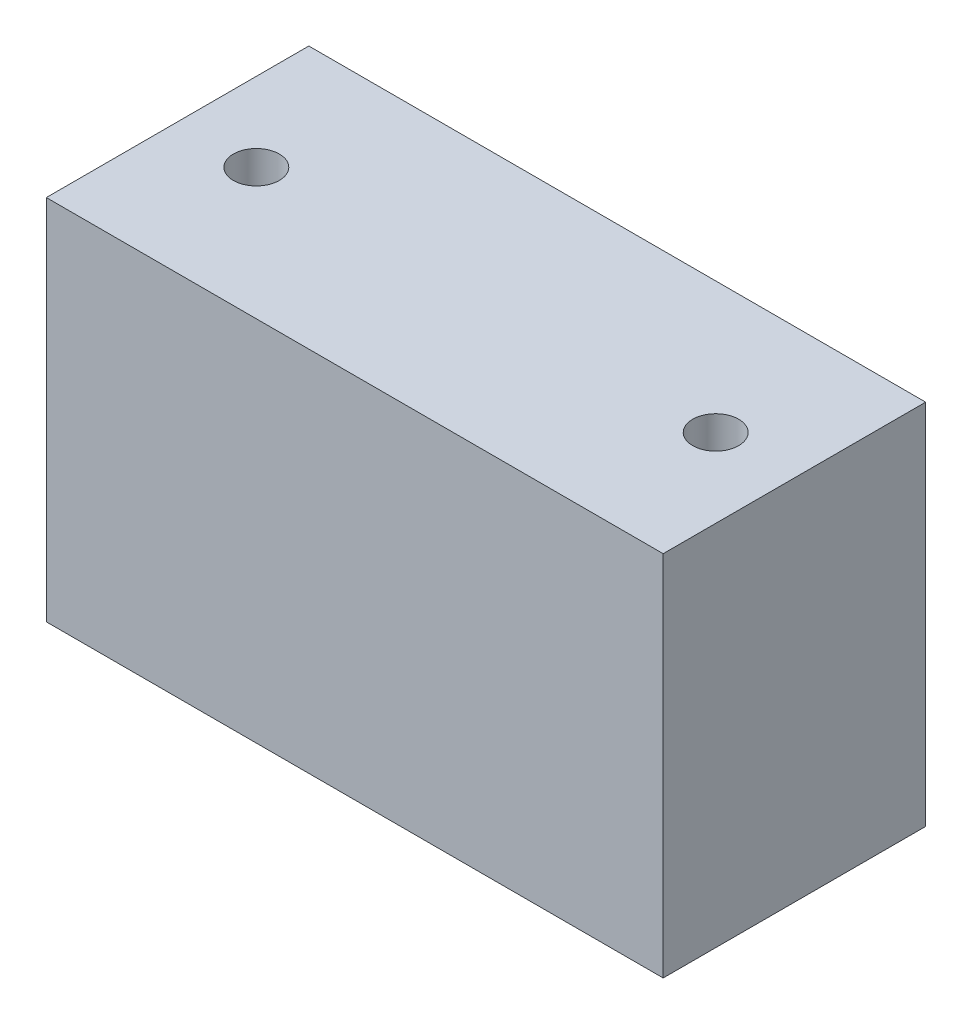
SolidWorks part; units mm, degrees
ref_plane "Front Plane" through (0, 0, 0) normal (0, 0, 1) x (1, 0, 0)
ref_plane "Top Plane" through (0, 0, 0) normal (0, 1, 0) x (1, 0, 0)
ref_plane "Right Plane" through (0, 0, 0) normal (1, 0, 0) x (0, 0, -1)
sketch "Sketch1" plane through (0, 0, 0) normal (0, 1, 0) x (1, 0, 0)
  line L1 (-23.5, 10) -> (23.5, 10)
  line L2 (-23.5, 10) -> (-23.5, -10)
  line L3 (-23.5, -10) -> (23.5, -10)
  line L4 (23.5, 10) -> (23.5, -10)
  line L5 (-23.5, 10) -> (23.5, -10) construction
  line L6 (-23.5, -10) -> (23.5, 10) construction
  point P0 (0, 0)
  dimension "D1" = 47
  dimension "D2" = 20
extrude "Boss-Extrude1" add sketch "Sketch1" along normal blind 28
sketch "Sketch2" plane through (0, 28, 0) normal (0, 1, 0) x (1, 0, 0)
  line L0 (0, 0) -> (0, 11.9138) construction
  circle A0 centre (-17.5, 0) radius 1.75
  circle A1 centre (17.5, 0) radius 1.75
  point P7 (0, 0)
  dimension "D1" = 3.5
  dimension "D2" = 3.5
  dimension "D3" = 17.5
  dimension "D4" = 17.5
extrude "Cut-Extrude1" cut sketch "Sketch2" against normal through all
